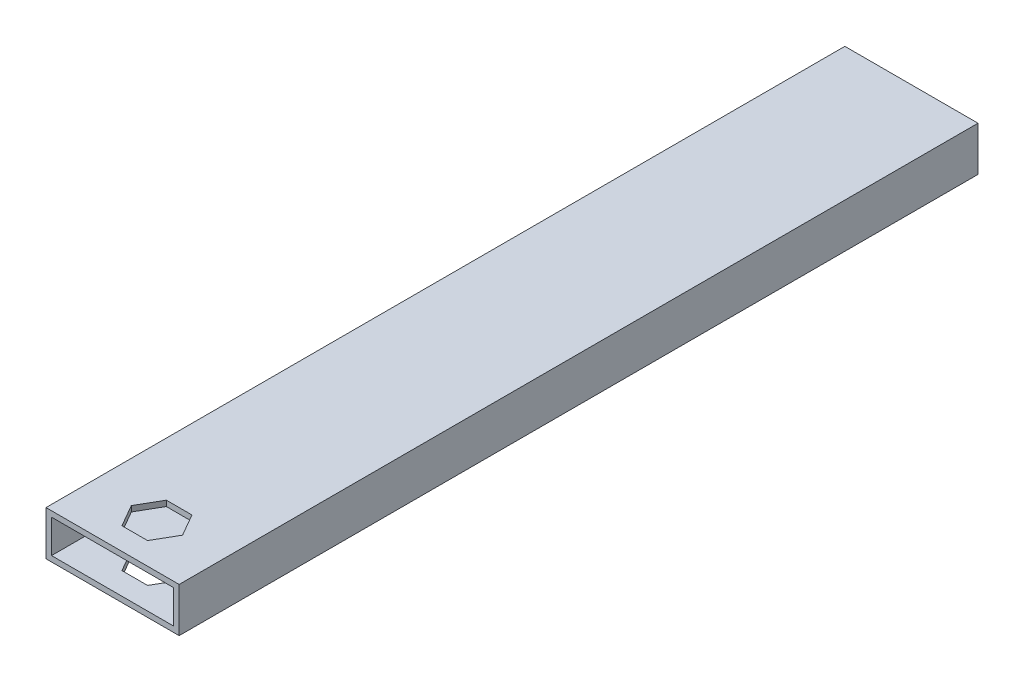
SolidWorks part; units mm, degrees
material "6061 Alloy"
ref_plane "Front Plane" through (0, 0, 0) normal (0, 0, 1) x (1, 0, 0)
ref_plane "Top Plane" through (0, 0, 0) normal (0, 1, 0) x (1, 0, 0)
ref_plane "Right Plane" through (0, 0, 0) normal (1, 0, 0) x (0, 0, -1)
sketch "Sketch1" plane through (0, 0, 0) normal (0, 0, 1) x (1, 0, 0)
  line L1 (0, 0) -> (38.1, 0)
  line L2 (0, 0) -> (0, 12.7)
  line L3 (0, 12.7) -> (38.1, 12.7)
  line L4 (38.1, 0) -> (38.1, 12.7)
  dimension "D1" = 38.1
  dimension "D2" = 12.7
extrude "Boss-Extrude1" add sketch "Sketch1" along normal blind 228.6
sketch "Sketch2" plane through (0, 0, 228.6) normal (0, 0, 1) x (1, 0, 0)
  line L4 (36.5125, 1.5875) -> (36.5125, 11.1125)
  line L5 (36.5125, 1.5875) -> (36.5125, 11.1125)
  line L6 (1.5875, 11.1125) -> (1.5875, 1.5875)
  line L7 (1.5875, 11.1125) -> (1.5875, 1.5875)
  line L8 (36.5125, 11.1125) -> (1.5875, 11.1125)
  line L9 (1.5875, 1.5875) -> (36.5125, 1.5875)
  line L10 (36.5125, 11.1125) -> (1.5875, 11.1125)
  line L13 (1.5875, 1.5875) -> (36.5125, 1.5875)
  dimension "D1" = 1.5875
extrude "Cut-Extrude1" cut sketch "Sketch2" against normal through all
sketch "Sketch3" plane through (0, 0, 0) normal (0, -1, 0) x (1, 0, 0)
  line L0 (38.1, 228.6) -> (38.1, 0) construction
  line L1 (26.3823, 215.9) -> (22.7162, 222.25)
  line L2 (22.7162, 222.25) -> (15.3838, 222.25)
  line L3 (15.3838, 222.25) -> (11.7177, 215.9)
  line L4 (11.7177, 215.9) -> (15.3838, 209.55)
  line L5 (15.3838, 209.55) -> (22.7162, 209.55)
  line L6 (22.7162, 209.55) -> (26.3823, 215.9)
  line L8 (0, 228.6) -> (38.1, 228.6) construction
  circle A0 centre (19.05, 215.9) radius 6.35 construction
  dimension "D3" = 12.7
  dimension "D1" = 19.05
  dimension "D2" = 12.7
extrude "Cut-Extrude2" cut sketch "Sketch3" against normal through all
